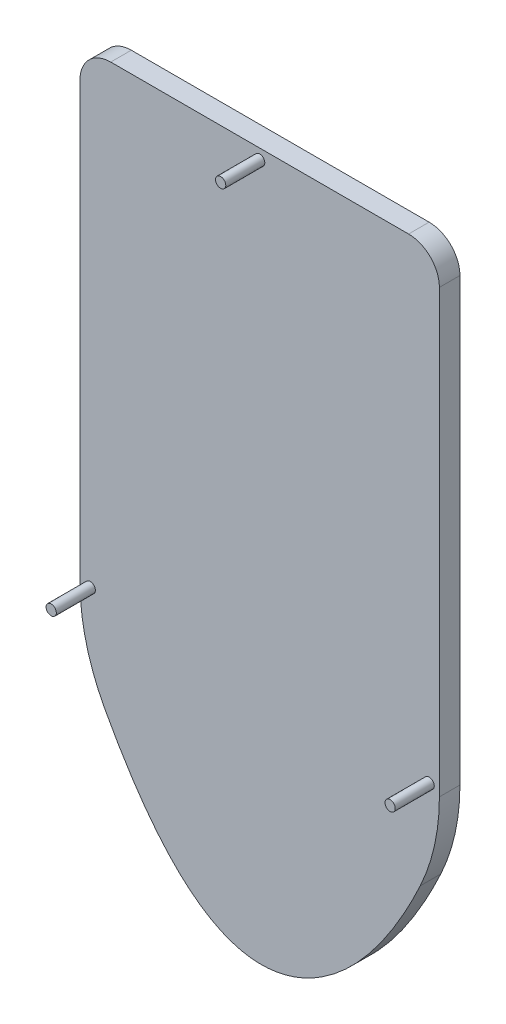
SolidWorks part; units mm, degrees
ref_plane "Front Plane" through (0, 0, 0) normal (0, 0, 1) x (1, 0, 0)
ref_plane "Top Plane" through (0, 0, 0) normal (0, 1, 0) x (1, 0, 0)
ref_plane "Right Plane" through (0, 0, 0) normal (1, 0, 0) x (0, 0, -1)
ref_plane "Plane1" through (0, 0, 2) normal (0, 0, 1) x (1, 0, 0)
sketch "Sketch1" plane through (0, 0, 2) normal (0, 0, 1) x (1, 0, 0)
  line L0 (7.7714, 22.5408) -> (-27.2286, 22.5408)
  line L1 (-27.2286, 22.5408) -> (-27.2286, -27.8131)
  line L2 (7.7714, -27.8501) -> (7.7714, 22.5408)
  spline S0 degree 3 poles (-27.2286, -27.8131) (-26.4279, -29.2958) (-25.6271, -30.7786) (-24.8263, -32.2613) (-19.8376, -41.4987) (-9.8975, -50.9523) (1.3923, -41.5601) (5.9046, -31.8621) (6.5269, -30.5248) (7.1491, -29.1874) (7.7714, -27.8501) knots 0 0 0 0 0.068638 0.068638 0.068638 0.496242 0.937654 0.937654 0.937654 0.998524 0.998524 0.998524 0.998524
extrude "Boss-Extrude1" add sketch "Sketch1" against normal blind 2
ref_plane "Plane2" through (0, -22.7576, 0) normal (0, -1, 0) x (1, 0, 0)
sketch "Sketch2" plane through (0, -22.7576, 0) normal (0, -1, 0) x (1, 0, 0)
  line L0 (7.2714, 5.8) -> (6.7714, 5.8)
  line L1 (6.7714, 5.8) -> (6.7714, 2)
  line L2 (6.7714, 2) -> (7.2714, 2)
  line L3 (7.2714, 2) -> (7.2714, 5.8)
  line L4 (6.7714, 5.8) -> (6.7714, 2) construction
revolve "Revolve1" add sketch "Sketch2" angle 360 about L4
sketch "Sketch3" plane through (0, -22.7576, 0) normal (0, -1, 0) x (1, 0, 0)
  line L0 (-25.7286, 5.8) -> (-26.2286, 5.8)
  line L1 (-26.2286, 5.8) -> (-26.2286, 2)
  line L2 (-26.2286, 2) -> (-25.7286, 2)
  line L3 (-25.7286, 2) -> (-25.7286, 5.8)
  line L4 (-26.2286, 5.8) -> (-26.2286, 2) construction
revolve "Revolve2" add sketch "Sketch3" angle 360 about L4
ref_plane "Plane3" through (0, 21.5408, 0) normal (0, -1, 0) x (1, 0, 0)
sketch "Sketch4" plane through (0, 21.5408, 0) normal (0, -1, 0) x (1, 0, 0)
  line L0 (-9.2286, 5.8) -> (-9.7286, 5.8)
  line L1 (-9.7286, 5.8) -> (-9.7286, 2)
  line L2 (-9.7286, 2) -> (-9.2286, 2)
  line L3 (-9.2286, 2) -> (-9.2286, 5.8)
  line L4 (-9.7286, 5.8) -> (-9.7286, 2) construction
revolve "Revolve3" add sketch "Sketch4" angle 360 about L4
fillet "Fillet1" radius 3 2 edges at (7.7714, 22.5408, 1) (-27.2286, 22.5408, 1)
fillet "Fillet2" radius 20 2 edges at (7.7714, -27.8501, 1) (-27.2286, -27.8131, 1)
